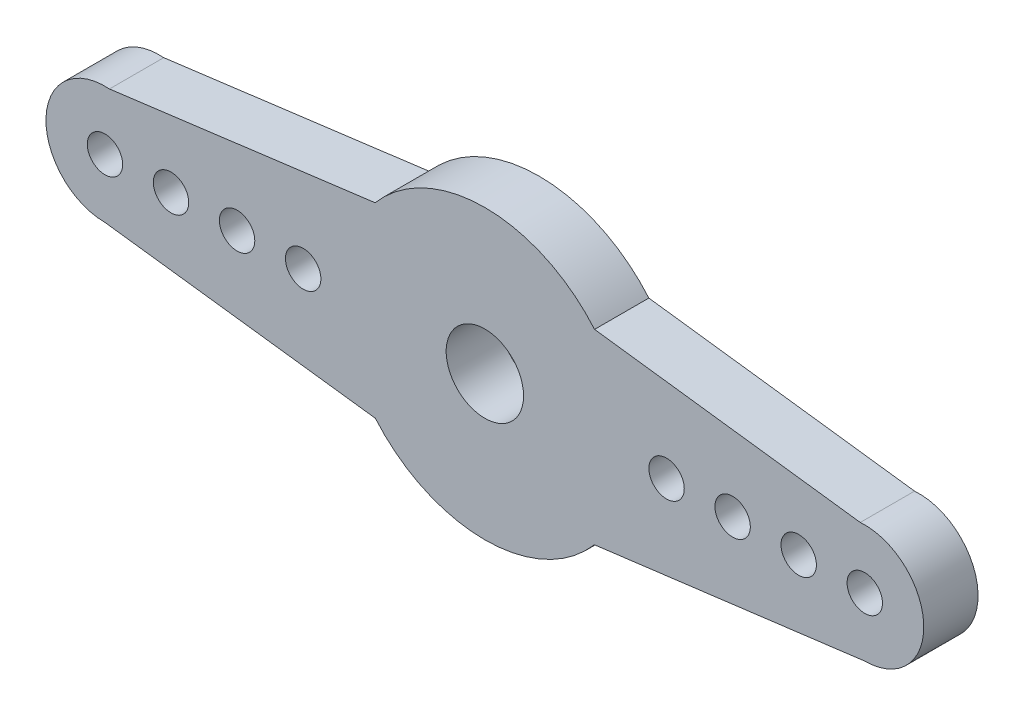
SolidWorks part; units mm, degrees
ref_plane "Front Plane" through (0, 0, 0) normal (0, 0, 1) x (1, 0, 0)
ref_plane "Top Plane" through (0, 0, 0) normal (0, 1, 0) x (1, 0, 0)
ref_plane "Right Plane" through (0, 0, 0) normal (1, 0, 0) x (0, 0, -1)
sketch "Sketch1" plane through (0, 0, 0) normal (0, 0, 1) x (1, 0, 0)
  line L0 (-16.1, 0) -> (16.1, 0)
  line L1 (0, 4.55) -> (15.9092, 2.4931)
  line L2 (0, -4.55) -> (16.1, -2.5004)
  line L3 (16.1, 0) -> (13.3, 0)
  line L4 (13.3, 0) -> (10.5, 0)
  line L5 (10.5, 0) -> (7.7, 0)
  line L6 (0, -6.1) -> (0, 6.1)
  line L7 (-10.5, 0) -> (-7.7, 0)
  line L8 (-13.3, 0) -> (-10.5, 0)
  line L9 (-16.1, 0) -> (-13.3, 0)
  line L10 (0, -4.55) -> (-16.1, -2.5004)
  line L11 (0, 4.55) -> (-15.9092, 2.4931)
  arc A0 (16.1, -2.5004) -> (15.9092, 2.4931) centre (16.1, 0) ccw
  circle A1 centre (0, 0) radius 6.1
  circle A3 centre (16.1, 0) radius 0.75
  circle A4 centre (13.3, 0) radius 0.75
  circle A5 centre (10.5, 0) radius 0.75
  circle A6 centre (7.7, 0) radius 0.75
  circle A7 centre (0, 0) radius 1.64
  circle A8 centre (-7.7, 0) radius 0.75
  circle A9 centre (-10.5, 0) radius 0.75
  circle A10 centre (-13.3, 0) radius 0.75
  circle A11 centre (-16.1, 0) radius 0.75
  arc A12 (-16.1, -2.5004) -> (-15.9092, 2.4931) centre (-16.1, 0) cw
extrude "Boss-Extrude1" add sketch "Sketch1" along normal blind 2.3
